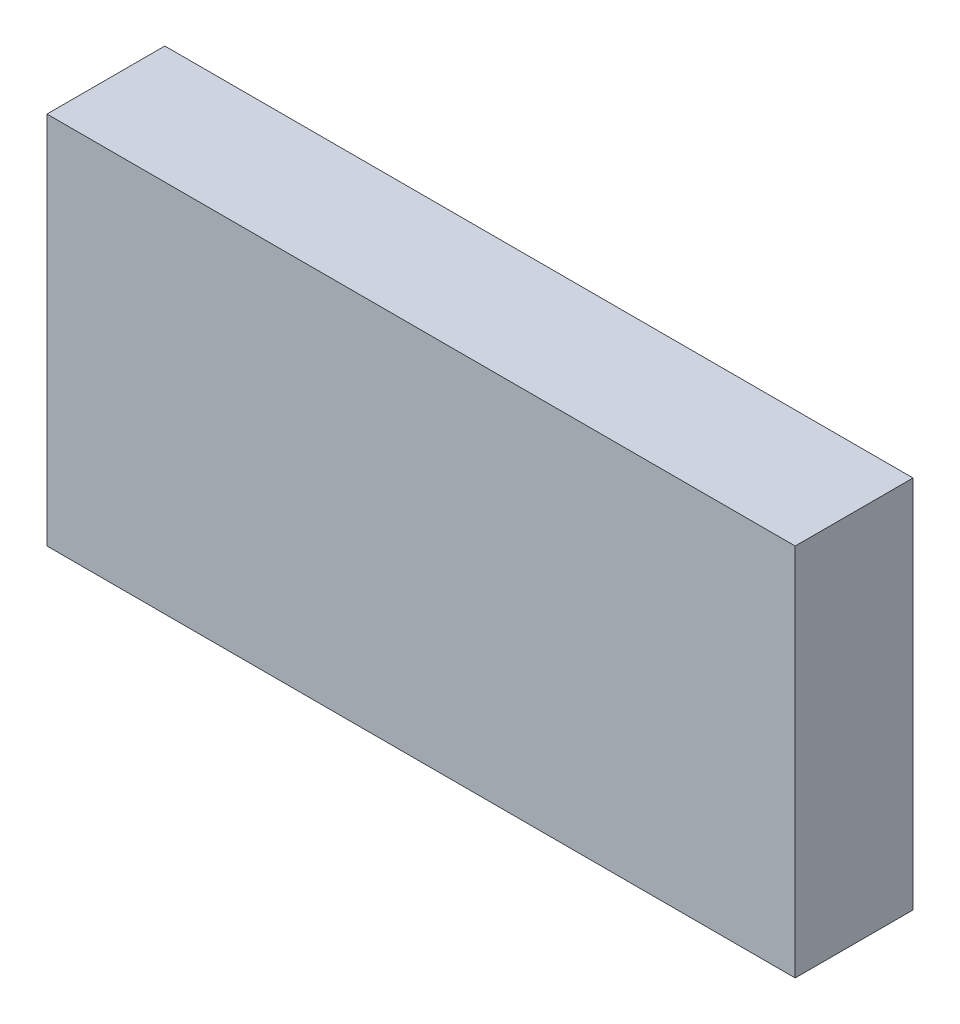
SolidWorks part; units mm, degrees
ref_plane "Front Plane" through (0, 0, 0) normal (0, 0, 1) x (1, 0, 0)
ref_plane "Top Plane" through (0, 0, 0) normal (0, 1, 0) x (1, 0, 0)
ref_plane "Right Plane" through (0, 0, 0) normal (1, 0, 0) x (0, 0, -1)
sketch "Sketch1" plane through (0, 0, 0) normal (0, 0, 1) x (1, 0, 0)
  line L1 (0, 0) -> (40, 0)
  line L2 (0, 0) -> (0, 20)
  line L3 (0, 20) -> (40, 20)
  line L4 (40, 0) -> (40, 20)
extrude "Boss-Extrude1" add sketch "Sketch1" along normal blind 6.3
